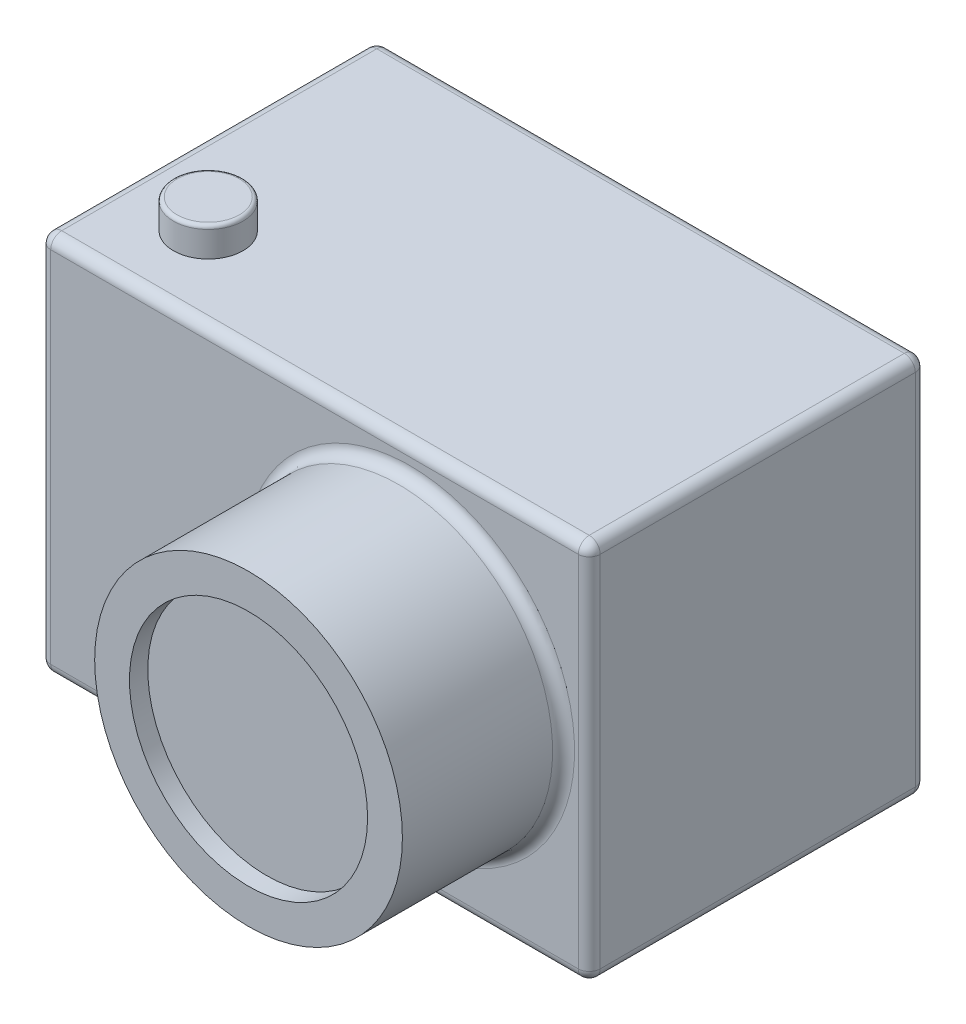
SolidWorks part; units mm, degrees
ref_plane "Front Plane" through (0, 0, 0) normal (0, 0, 1) x (1, 0, 0)
ref_plane "Top Plane" through (0, 0, 0) normal (0, 1, 0) x (1, 0, 0)
ref_plane "Right Plane" through (0, 0, 0) normal (1, 0, 0) x (0, 0, -1)
sketch "Sketch1" plane through (0, 0, 0) normal (0, 0, 1) x (1, 0, 0)
  line L1 (0, 0) -> (150, 0)
  line L2 (0, 0) -> (0, 104)
  line L3 (0, 104) -> (150, 104)
  line L4 (150, 0) -> (150, 104)
  dimension "D1" = 150
  dimension "D2" = 104
extrude "Boss-Extrude1" add sketch "Sketch1" against normal blind 92
sketch "Sketch2" plane through (0, 0, 0) normal (0, 0, 1) x (1, 0, 0)
  line L0 (150, 0) -> (150, 104) construction
  line L2 (150, 104) -> (0, 104) construction
  circle A0 centre (101, 54) radius 42
  dimension "D1" = 84
  dimension "D2" = 49
  dimension "D3" = 50
extrude "Boss-Extrude2" add sketch "Sketch2" along normal blind 44
sketch "Sketch3" plane through (0, 0, -92) normal (0, 0, -1) x (-1, 0, 0)
  line L0 (0, 0) -> (-150, 0) construction
  line L1 (-150, 0) -> (-150, 104) construction
  point P8 (-75, 52)
  dimension "D1" = 52
  dimension "D2" = 75
sketch "Sketch4" plane through (0, 104, 0) normal (0, 1, 0) x (1, 0, 0)
  line L0 (0, 46) -> (150, 46) construction
  line L1 (0, 92) -> (0, 0) construction
  line L2 (150, 92) -> (150, 0) construction
  point P6 (75, 46)
fillet "Fillet1" radius 3 12 edges at (150, 52, -92) (150, 0, -46) (150, 52, 0) (0, 104, -46) (75, 104, -92) (150, 104, -46) (75, 104, 0) (0, 0, -46) (75, 0, -92) (0, 52, -92) (75, 0, 0) (0, 52, 0)
fillet "Fillet2" radius 3 1 edges at (143, 54, 0)
sketch "Sketch5" plane through (0, 104, 0) normal (0, 1, 0) x (1, 0, 0)
  line L0 (3, 3) -> (147, 3) construction
  line L1 (3, 89) -> (3, 3) construction
  circle A0 centre (23, 23) radius 9.5
  dimension "D3" = 19
  dimension "D1" = 20
  dimension "D2" = 20
extrude "Boss-Extrude3" add sketch "Sketch5" along normal blind 8
fillet "Fillet3" radius 1 1 edges at (23, 112, -13.5)
sketch "Sketch6" plane through (0, 0, 44) normal (0, 0, 1) x (1, 0, 0)
  circle A0 centre (101, 54) radius 32.5
  dimension "D1" = 65
extrude "Cut-Extrude1" cut sketch "Sketch6" against normal blind 5
